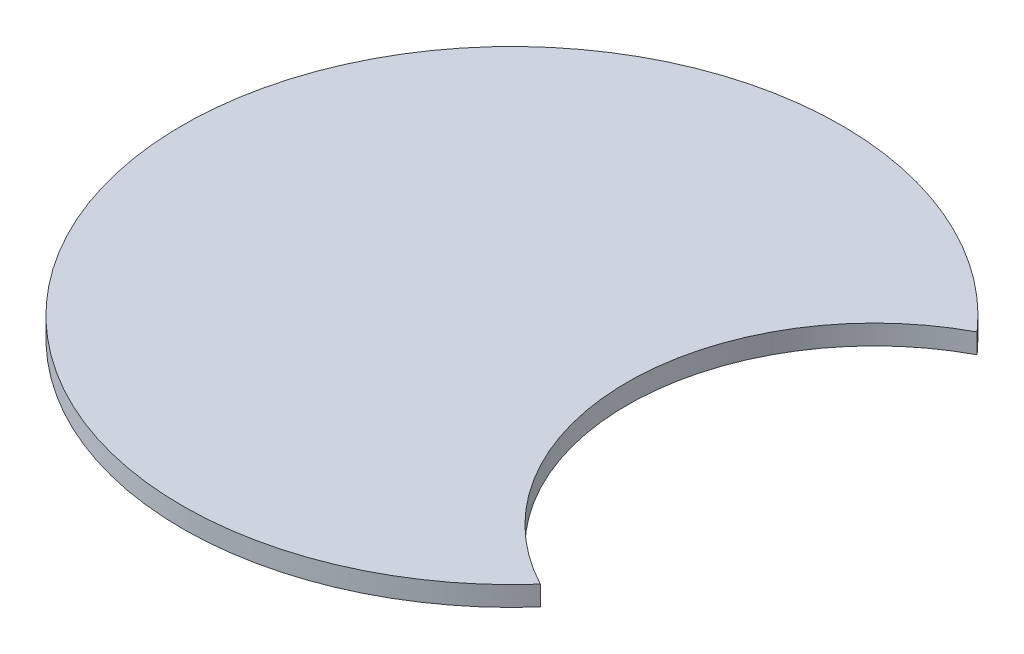
SolidWorks part; units mm, degrees
ref_plane "Front Plane" through (0, 0, 0) normal (0, 0, 1) x (1, 0, 0)
ref_plane "Top Plane" through (0, 0, 0) normal (0, 1, 0) x (1, 0, 0)
ref_plane "Right Plane" through (0, 0, 0) normal (1, 0, 0) x (0, 0, -1)
sketch "Sketch1" plane through (0, 0, 0) normal (0, 1, 0) x (1, 0, 0)
  arc A0 (37.4432, 33.1362) -> (37.4432, -33.1362) centre (0, 0) ccw
  arc A1 (37.4432, 33.1362) -> (37.4432, -33.1362) centre (55, 0) ccw
  point P5 (0, 0)
  dimension "D1" = 100
  dimension "D2" = 75
  dimension "D3" = 55
extrude "Boss-Extrude1" add sketch "Sketch1" along normal blind 3
